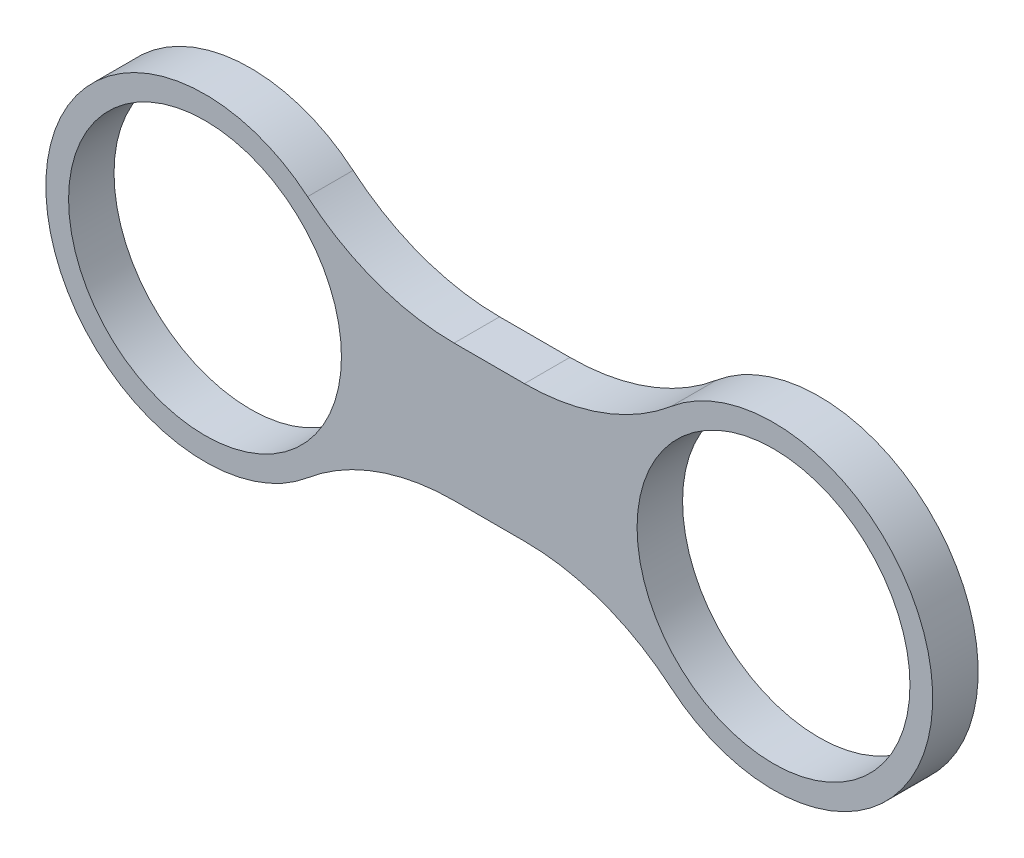
SolidWorks part; units mm, degrees
ref_plane "Front Plane" through (0, 0, 0) normal (0, 0, 1) x (1, 0, 0)
ref_plane "Top Plane" through (0, 0, 0) normal (0, 1, 0) x (1, 0, 0)
ref_plane "Right Plane" through (0, 0, 0) normal (1, 0, 0) x (0, 0, -1)
sketch "Sketch1" plane through (0, 0, 0) normal (0, 0, 1) x (1, 0, 0)
  line L0 (-12.5, 0) -> (12.5, 0) construction
  line L1 (-12.5, 6) -> (12.5, 6) construction
  line L2 (-12.5, -6) -> (12.5, -6) construction
  line L3 (-9.1947, 3) -> (9.8682, 3)
  line L4 (-9.1947, -3) -> (9.8682, -3)
  arc A0 (-12.5, 6) -> (-12.5, -6) centre (-12.5, 0) ccw construction
  arc A1 (12.5, -6) -> (12.5, 6) centre (12.5, 0) ccw construction
  circle A2 centre (-12.5, 0) radius 7
  circle A3 centre (12.5, 0) radius 7
  arc A4 (-12.5, 6) -> (-12.5, -6) centre (-12.5, 0) cw
  circle A5 centre (12.5, 0) radius 6
  arc A6 (-12.5, 6) -> (-12.5, -6) centre (-12.5, 0) ccw
  point P2 (0, 0)
  dimension "D2" = 6
  dimension "D3" = 14
  dimension "D4" = 6
  dimension "D1" = 25
extrude "Boss-Extrude1" add sketch "Sketch1" along normal blind 2 contours L1 A2 L2 A0 | A4 L0 A2 L1 | L0 A4 L2 A2 | L0 A2 L2 A3 | A2 L0 A3 L1 | L2 A3 L1 A1 | A3 L0 A5 L1 | L0 A3 L2 A5
fillet "Fillet1" radius 10 4 edges at (6.1754, 3, 1) (6.1754, -3, 1) (-6.1754, -3, 1) (-6.1754, 3, 1)
